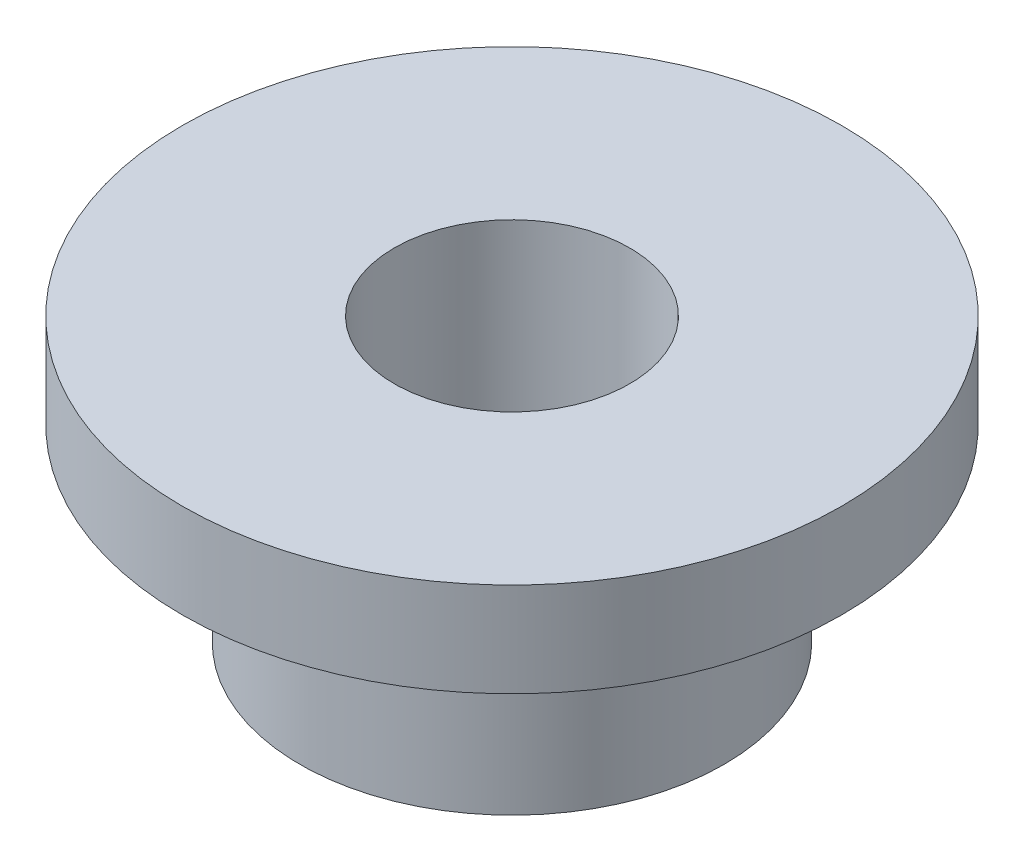
SolidWorks part; units mm, degrees
ref_plane "前视基准面" through (0, 0, 0) normal (0, 0, 1) x (1, 0, 0)
ref_plane "上视基准面" through (0, 0, 0) normal (0, 1, 0) x (1, 0, 0)
ref_plane "右视基准面" through (0, 0, 0) normal (1, 0, 0) x (0, 0, -1)
other "Configuration Table"
sketch "草图1" plane through (0, 0, 0) normal (0, 0, 1) x (1, 0, 0)
  line L6 (0, 0) -> (18, 0)
  line L7 (18, 0) -> (18, -8)
  line L8 (18, -8) -> (8, -8)
  line L9 (8, -8) -> (8, -24)
  line L10 (8, -24) -> (0, -24)
  line L11 (0, -24) -> (0, 0)
  line L12 (-10, 2.6965) -> (-10, -29.312) construction
  dimension "D1" = 24
  dimension "D2" = 18
  dimension "D3" = 10
  dimension "D4" = 18
  dimension "D5" = 8
revolve "旋转1" add sketch "草图1" angle 360 about L12
